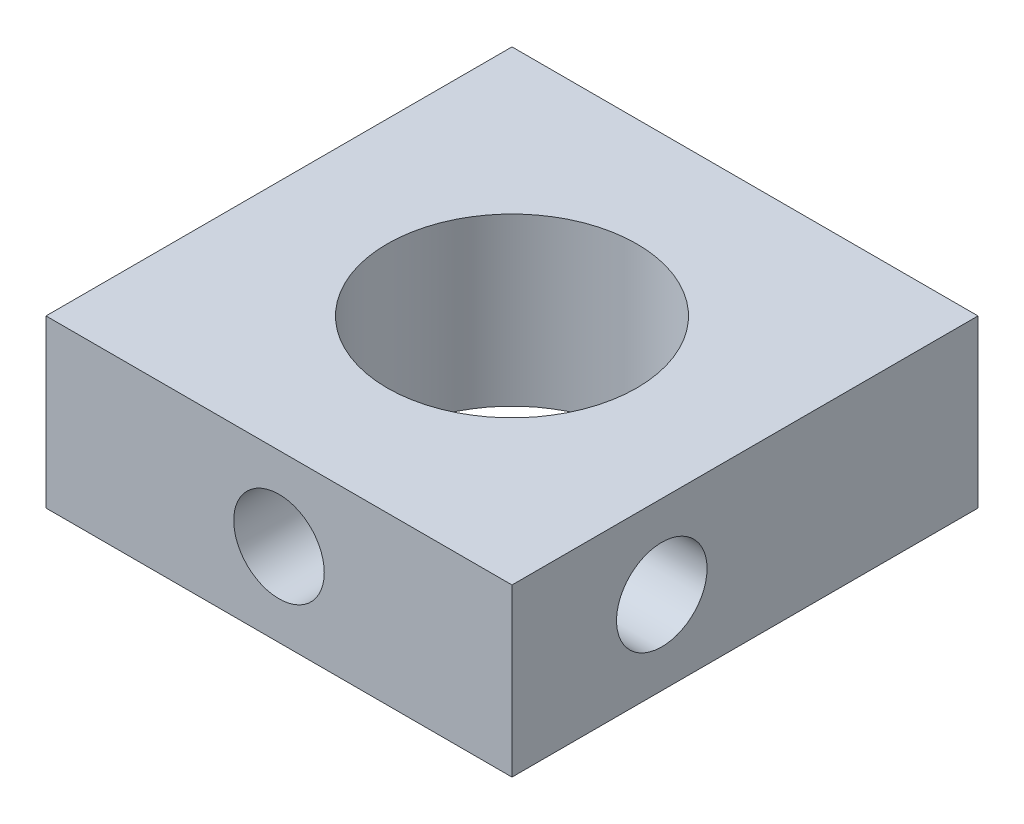
SolidWorks part; units mm, degrees
ref_plane "Front Plane" through (0, 0, 0) normal (0, 0, 1) x (1, 0, 0)
ref_plane "Top Plane" through (0, 0, 0) normal (0, 1, 0) x (1, 0, 0)
ref_plane "Right Plane" through (0, 0, 0) normal (1, 0, 0) x (0, 0, -1)
sketch "Sketch1" plane through (0, 0, 0) normal (0, 1, 0) x (1, 0, 0)
  line L1 (-8.89, -8.89) -> (8.89, -8.89)
  line L2 (-8.89, -8.89) -> (-8.89, 8.89)
  line L3 (-8.89, 8.89) -> (8.89, 8.89)
  line L4 (8.89, -8.89) -> (8.89, 8.89)
  line L5 (-8.89, -8.89) -> (8.89, 8.89) construction
  line L6 (-8.89, 8.89) -> (8.89, -8.89) construction
  circle A0 centre (0, 0) radius 4.7625
  dimension "D1" = 9.525
  dimension "D2" = 17.78
  dimension "D3" = 17.78
extrude "Boss-Extrude1" add sketch "Sketch1" along normal blind 6.35
sketch "Sketch2" plane through (0, 0, 8.89) normal (0, 0, 1) x (1, 0, 0)
  line L0 (0, -3.4925) -> (0, 3.4925) construction
  line L1 (-8.89, 6.35) -> (-8.89, 0) construction
  point P0 (0, 3.175)
  point P1 (0, 0)
  point P4 (0, 0)
  point P7 (-8.89, 3.175)
hole_wizard "#8-32 Tapped Hole1" positions "Sketch3" profile "Sketch4" tap size "#8-32" standard "ANSI Inch"
sketch "Sketch3" plane through (0, 0, 8.89) normal (0, 0, 1) x (1, 0, 0)
  point P0 (0, 3.175)
sketch "Sketch4" plane through (0, 3.175, 8.89) normal (1, 0, 0) x (0, -1, 0)
  line L0 (0, 0) -> (0, 10.668)
  line L1 (0, 10.668) -> (1.7272, 9.6302)
  line L2 (1.7272, 9.6302) -> (1.7272, 0)
  line L5 (1.7272, 0) -> (0, 0)
  line L10 (0, 10.668) -> (-1.7272, 9.6302) construction
  line L11 (0, -6.35) -> (0, 107.95) construction
  dimension "Tap Drill Dia." = 3.4544
  dimension "Tap Drill Depth" = 10.668
  dimension "Drill Angle" = 118
cosmetic thread "Hole Thread1" parameters "D1"=8.382, "D2"=4.1656
sketch "Sketch5" plane through (-8.89, 0, 0) normal (-1, 0, 0) x (0, 0, 1)
  line L1 (0, -3.4925) -> (0, 3.4925) construction
  point P0 (3.175, 3.175)
  point P1 (0, 0)
  point P3 (0, 0)
  point P4 (3.1624, 3.175)
  point P6 (0, 0)
  dimension "D1" = 3.175
hole_wizard "#8-32 Tapped Hole2" positions "Sketch6" profile "Sketch7" tap size "#8-32" standard "ANSI Inch"
sketch "Sketch6" plane through (-8.89, 0, 0) normal (-1, 0, 0) x (0, 0, 1)
  point P0 (3.175, 3.175)
cosmetic thread "Hole Thread2" parameters "D2"=4.1656
sketch "Sketch7" plane through (-8.89, 3.175, 3.175) normal (0, 1, 0) x (0, 0, 1)
  line L0 (0, 0) -> (0, 4.8478)
  line L1 (0, 4.8478) -> (1.7272, 3.81)
  line L2 (1.7272, 3.81) -> (1.7272, 0)
  line L5 (1.7272, 0) -> (0, 0)
  line L10 (0, 4.8478) -> (-1.7272, 3.81) construction
  line L11 (0, -6.35) -> (0, 107.95) construction
  dimension "Tap Drill Dia." = 3.4544
  dimension "Tap Drill Depth" = 3.81
  dimension "Drill Angle" = 118
mirror "Mirror1" about plane through (0, 0, 0) normal (1, 0, 0) of "#8-32 Tapped Hole2"
cosmetic thread "Hole Thread3" parameters "D2"=4.1656
